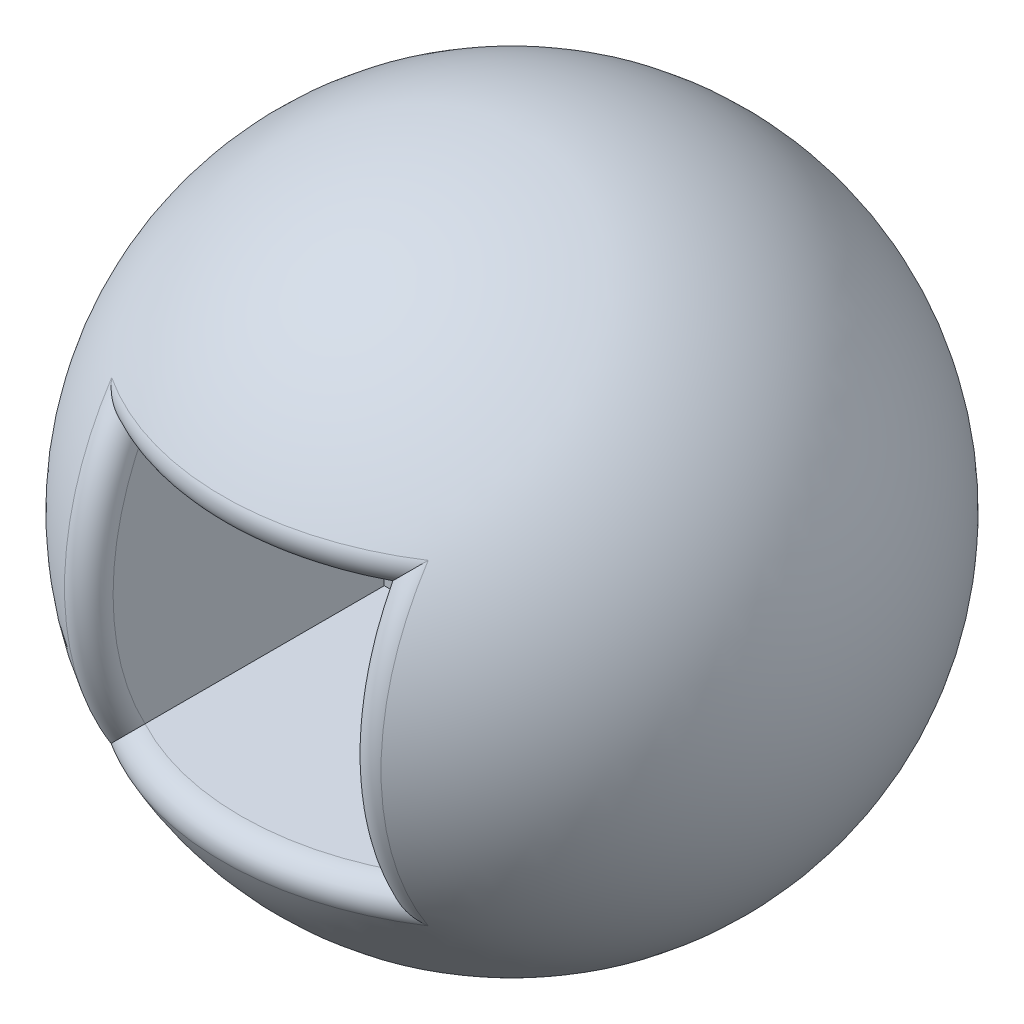
SolidWorks part; units mm, degrees
ref_plane "정면" through (0, 0, 0) normal (0, 0, 1) x (1, 0, 0)
ref_plane "윗면" through (0, 0, 0) normal (0, 1, 0) x (1, 0, 0)
ref_plane "우측면" through (0, 0, 0) normal (1, 0, 0) x (0, 0, -1)
sketch "스케치1" plane through (0, 0, 0) normal (0, 0, 1) x (1, 0, 0)
  line L0 (0, 8) -> (0, -8)
  arc A0 (0, -8) -> (0, 8) centre (0, 0) ccw
  dimension "D1" = 16
revolve "회전2" add sketch "스케치1" angle 360 about L0
ref_plane "평면1" through (0, 0, 8) normal (0, 0, 1) x (1, 0, 0)
sketch "스케치2" plane through (0, 0, 8) normal (0, 0, 1) x (1, 0, 0)
  line L1 (-3.1, 3.1) -> (3.1, 3.1)
  line L2 (-3.1, 3.1) -> (-3.1, -3.1)
  line L3 (-3.1, -3.1) -> (3.1, -3.1)
  line L4 (3.1, 3.1) -> (3.1, -3.1)
  point P7 (0, 3.1)
  point P9 (3.1, 0)
  dimension "D1" = 6.2
extrude "컷-돌출1" cut sketch "스케치2" along direction (0, 0, 1) on the side against the normal up to surface (8 mm away) up to plane "정면"
fillet "필렛1" radius 0.5 4 edges at (0, -3.1, 7.375) (3.1, 0, 7.375) (-3.1, 0, 7.375) (0, 3.1, 7.375)
